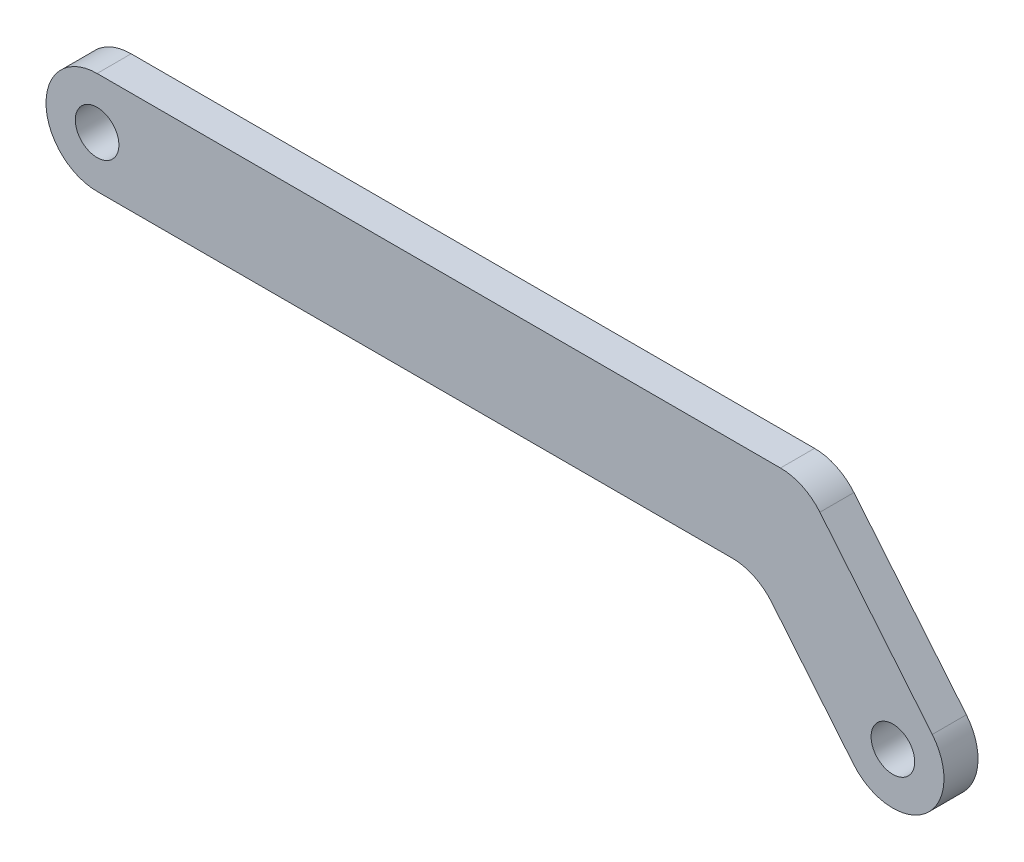
SolidWorks part; units mm, degrees
ref_plane "Front Plane" through (0, 0, 0) normal (0, 0, 1) x (1, 0, 0)
ref_plane "Top Plane" through (0, 0, 0) normal (0, 1, 0) x (1, 0, 0)
ref_plane "Right Plane" through (0, 0, 0) normal (1, 0, 0) x (0, 0, -1)
sketch "Sketch1" plane through (0, 0, 0) normal (0, 0, 1) x (1, 0, 0)
  line L0 (-74.1772, 17.4625) -> (-10.4775, 17.4625)
  line L1 (-6.8038, 15.7308) -> (3.6737, 3.0308)
  line L3 (-14.9675, 7.9375) -> (-74.1772, 7.9375)
  line L4 (-11.2938, 6.2058) -> (-3.6737, -3.0308)
  circle A0 centre (0, 0) radius 2.032
  circle A1 centre (-74.1772, 12.7) radius 2.032
  arc A2 (-74.1772, 17.4625) -> (-74.1772, 7.9375) centre (-74.1772, 12.7) ccw
  arc A4 (-11.2938, 6.2058) -> (-14.9675, 7.9375) centre (-14.9675, 3.175) ccw
  arc A5 (-6.8038, 15.7308) -> (-10.4775, 17.4625) centre (-10.4775, 12.7) ccw
  arc A8 (-3.6737, -3.0308) -> (3.6737, 3.0308) centre (0, 0) ccw
  point P5 (-10.4775, 12.7)
  point P9 (-14.1411, 3.0308)
  point P11 (-6.357, 15.9099)
  point P14 (-13.4575, 6.5684)
  dimension "D1" = 75.2565
  dimension "D2" = 4.064
  dimension "D3" = 4.7625
  dimension "D4" = 12.7
  dimension "D5" = 10.4775
  dimension "D6" = 12.7
extrude "Boss-Extrude1" add sketch "Sketch1" along normal blind 3.175
